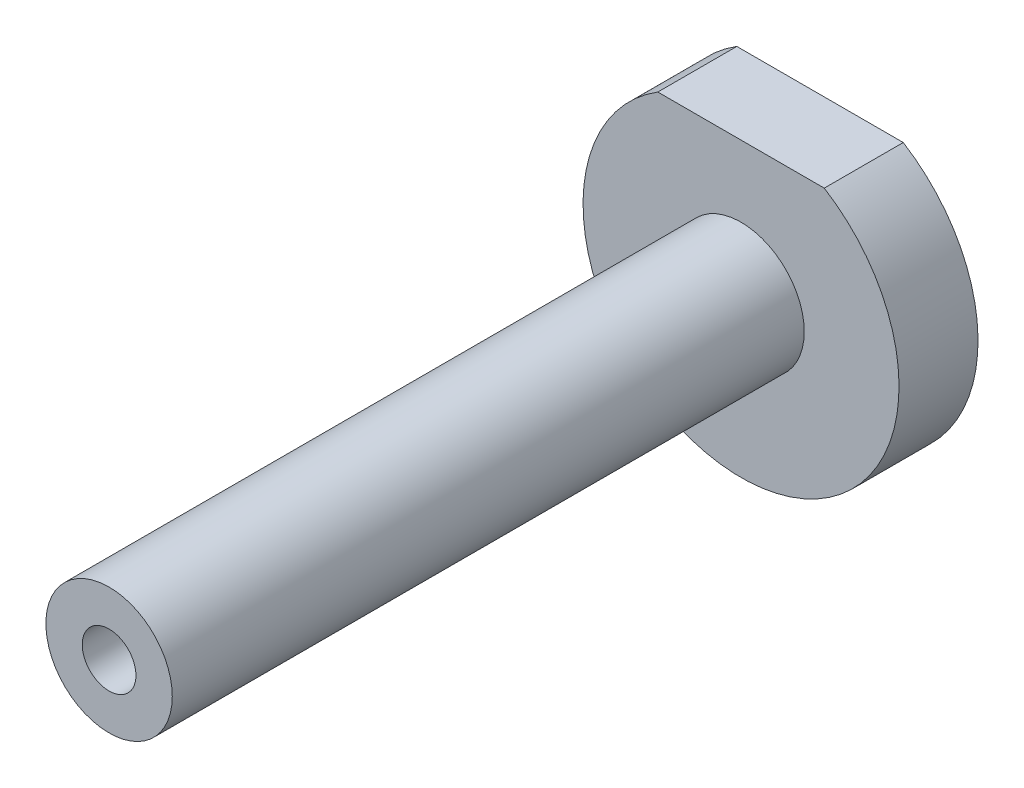
SolidWorks part; units mm, degrees
ref_plane "Plan de face" through (0, 0, 0) normal (0, 0, 1) x (1, 0, 0)
ref_plane "Plan de dessus" through (0, 0, 0) normal (0, 1, 0) x (1, 0, 0)
ref_plane "Plan de droite" through (0, 0, 0) normal (1, 0, 0) x (0, 0, -1)
sketch "Esquisse1" plane through (0, 0, 0) normal (0, 0, 1) x (1, 0, 0)
  circle A0 centre (0, 0) radius 20
  dimension "D1" = 40
extrude "Boss.-Extru.1" add sketch "Esquisse1" along normal blind 10
sketch "Esquisse2" plane through (0, 0, 10) normal (0, 0, 1) x (1, 0, 0)
  circle A0 centre (0, 0) radius 8
  dimension "D1" = 16
extrude "Boss.-Extru.2" add sketch "Esquisse2" along normal blind 80
sketch "Esquisse3" plane through (0, 0, 0) normal (0, 0, 1) x (1, 0, 0)
  line L1 (-18.1731, 23) -> (18.1731, 23)
  line L2 (-18.1731, 23) -> (-18.1731, 17)
  line L3 (-18.1731, 17) -> (18.1731, 17)
  line L4 (18.1731, 23) -> (18.1731, 17)
  line L5 (-18.1731, 23) -> (18.1731, 17) construction
  line L6 (-18.1731, 17) -> (18.1731, 23) construction
  circle A0 centre (0, 0) radius 20 construction
  point P0 (0, 20)
  dimension "D1" = 17
extrude "Enlèv. mat.-Extru.3" cut sketch "Esquisse3" along normal blind 41 contours L2 L1 L4 L3
sketch "Esquisse4" plane through (0, 0, 90) normal (0, 0, 1) x (1, 0, 0)
  circle A0 centre (0, 0) radius 1.818
hole_wizard "Trou taraudé M81" positions "Esquisse3D1" profile "Esquisse5" tap size "M8" standard "ISO"
sketch3d "Esquisse3D1"
  point P0 (0, 0, 0)
  point P4 (0, 0, 0)
  point P6 (0, 0, 90)
sketch "Esquisse5" plane through (0, 0, 90) normal (1, 0, 0) x (0, -1, 0)
  line L0 (0, 0) -> (0, 24.2929)
  line L1 (0, 24.2929) -> (3.4, 22.25)
  line L2 (3.4, 22.25) -> (3.4, 0)
  line L5 (3.4, 0) -> (0, 0)
  line L10 (0, 24.2929) -> (-3.4, 22.25) construction
  line L11 (0, -6.35) -> (0, 107.95) construction
  dimension "Diamètre du trou pour taraudage" = 6.8
  dimension "Profondeur du trou pour taraudage" = 22.25
  dimension "Angle de pointe" = 118
cosmetic thread "Filetage de perçage1" parameters "D1"=16, "D2"=8
cosmetic thread "Filetage de perçage2" parameters "D1"=16, "D2"=8
cosmetic thread "Filetage de perçage3" parameters "D1"=16, "D2"=8
